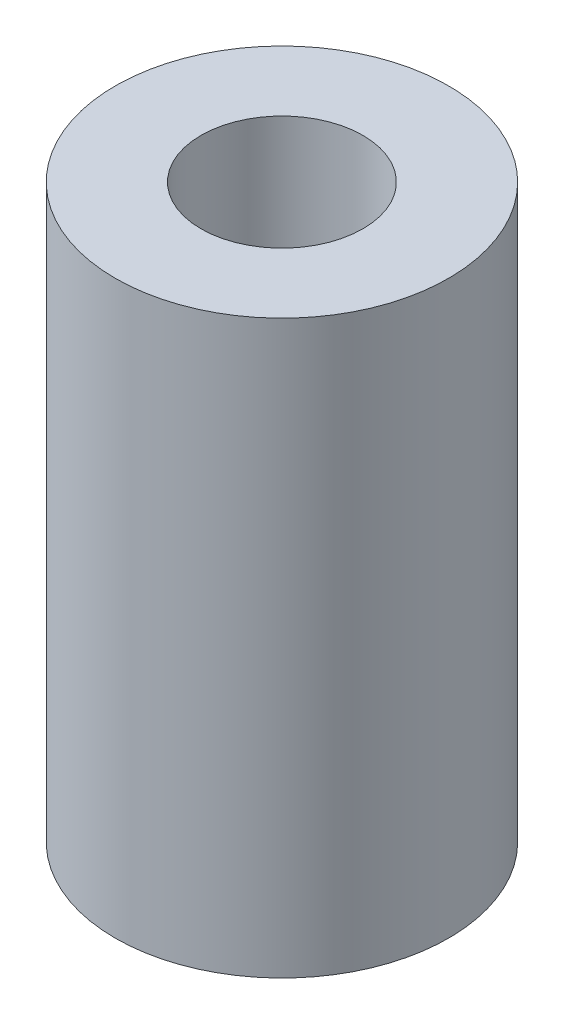
SolidWorks part; units mm, degrees
ref_plane "Front Plane" through (0, 0, 0) normal (0, 0, 1) x (1, 0, 0)
ref_plane "Top Plane" through (0, 0, 0) normal (0, 1, 0) x (1, 0, 0)
ref_plane "Right Plane" through (0, 0, 0) normal (1, 0, 0) x (0, 0, -1)
sketch "Sketch1" plane through (0, 0, 0) normal (0, 1, 0) x (1, 0, 0)
  circle A0 centre (0, 0) radius 1.7
  circle A1 centre (0, 0) radius 3.5
  dimension "D1" = 3.4
  dimension "D2" = 7
extrude "Boss-Extrude1" add sketch "Sketch1" along normal blind 12 contours A1 | A0
